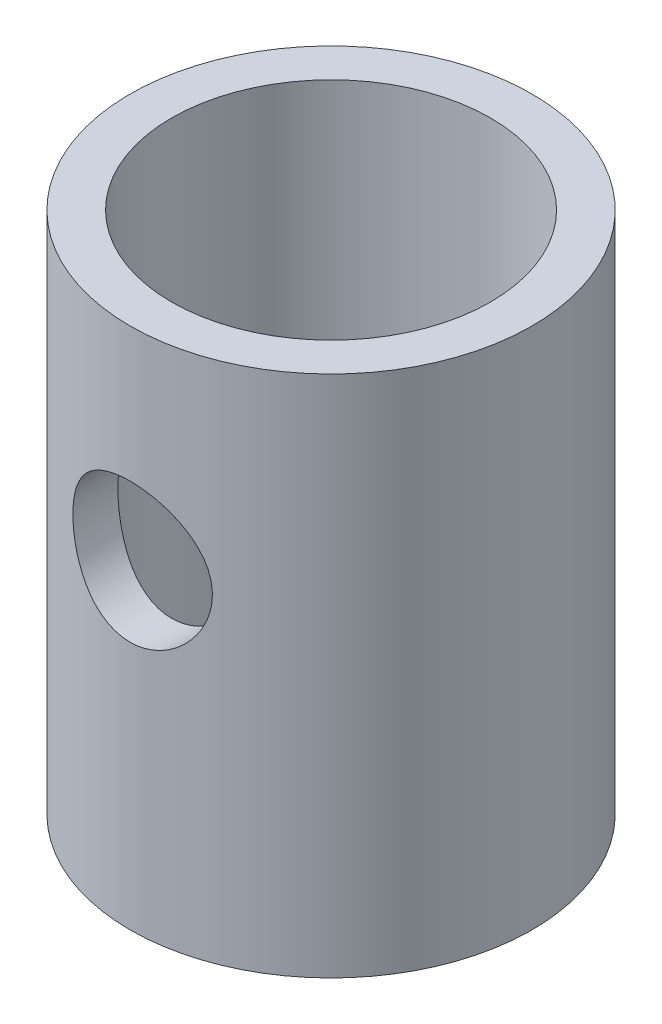
SolidWorks part; units mm, degrees
material "AISI 1020"
ref_plane "Front Plane" through (0, 0, 0) normal (0, 0, 1) x (1, 0, 0)
ref_plane "Top Plane" through (0, 0, 0) normal (0, 1, 0) x (1, 0, 0)
ref_plane "Right Plane" through (0, 0, 0) normal (1, 0, 0) x (0, 0, -1)
sketch "Sketch1" plane through (0, 0, 0) normal (0, 1, 0) x (1, 0, 0)
  circle A0 centre (0, 0) radius 8.001
  circle A1 centre (0, 0) radius 6.35
  dimension "D1" = 16.002
  dimension "D2" = 12.7
extrude "Boss-Extrude1" add sketch "Sketch1" along normal blind 20.828
ref_plane "Plane1" through (0, 0, 8.001) normal (0, 0, 1) x (1, 0, 0)
sketch "Sketch2" plane through (0, 0, 8.001) normal (0, 0, 1) x (1, 0, 0)
  line L0 (-8.001, 0) -> (8.001, 0) construction
  circle A0 centre (0, 12.7) radius 2.7788
  dimension "D1" = 12.7
  dimension "D2" = 5.5575
extrude "Cut-Extrude1" cut sketch "Sketch2" against normal blind 6.35
